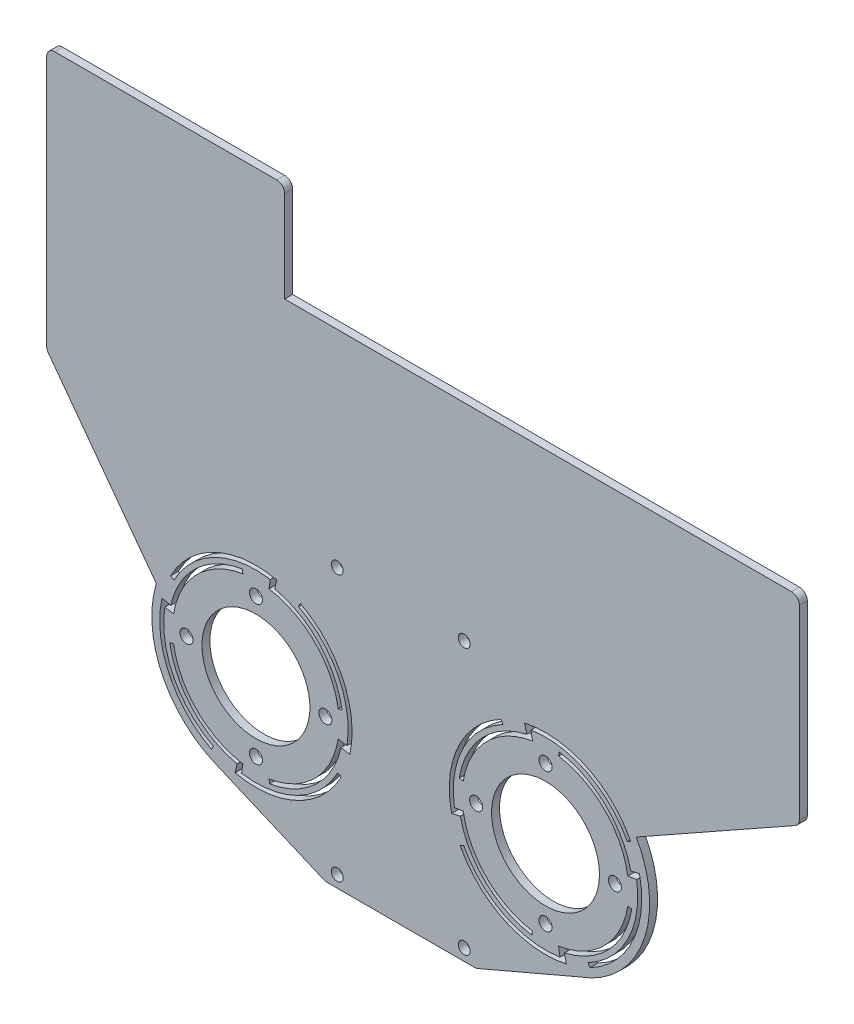
SolidWorks part; units mm, degrees
material "Thornel Mat VMA"
ref_plane "前视基准面" through (0, 0, 0) normal (0, 0, 1) x (1, 0, 0)
ref_plane "上视基准面" through (0, 0, 0) normal (0, 1, 0) x (1, 0, 0)
ref_plane "右视基准面" through (0, 0, 0) normal (1, 0, 0) x (0, 0, -1)
other "Configuration Table"
sketch "草图1" plane through (0, 0, 0) normal (0, 0, 1) x (1, 0, 0)
  line L0 (0, 0) -> (0, -46.0913) construction
  circle A0 centre (36.5, 0) radius 13.6
  circle A2 centre (36.5, 0) radius 21
  circle A5 centre (36.5, 0) radius 17.5 construction
  circle A6 centre (19, 0) radius 1.65
  circle A7 centre (36.5, 17.5) radius 1.65
  circle A8 centre (54, 0) radius 1.65
  circle A9 centre (36.5, -17.5) radius 1.65
  circle A14 centre (-36.5, 0) radius 17.5 construction
  circle A15 centre (-36.5, -17.5) radius 1.65
  circle A16 centre (-54, 0) radius 1.65
  circle A17 centre (-36.5, 17.5) radius 1.65
  circle A18 centre (-19, 0) radius 1.65
  circle A19 centre (-36.5, 0) radius 21
  circle A20 centre (-36.5, 0) radius 13.6
  point P20 (36.5, 0)
  point P28 (-36.5, 0)
  dimension "D3" = 42
  dimension "D4" = 27.2
  dimension "D5" = 35
  dimension "D6" = 4
  dimension "D1" = 73
  dimension "D2" = 36.5
extrude "凸台-拉伸1" add sketch "草图1" along normal blind 2
sketch "草图2" plane through (0, 0, 0) normal (0, 0, 1) x (1, 0, 0)
  line L0 (0, 0) -> (91.6352, 0) construction
  line L1 (36.5, 42.5304) -> (36.5, -42.8939) construction
  line L2 (39.9416, 21.7291) -> (39.7851, 20.7415)
  line L3 (32.8629, 22.9638) -> (33.2149, 20.7415)
  line L4 (36.5, 0) -> (21.2631, 41.8632) construction
  line L5 (31.2513, 23.6752) -> (31.7383, 21.4785)
  line L6 (25.3026, 21.51) -> (25.7643, 20.623)
  line L7 (58.2291, -3.4416) -> (57.2415, -3.2851)
  line L8 (59.4638, 3.6371) -> (57.2415, 3.2851)
  line L9 (33.0584, -21.7291) -> (33.2149, -20.7415)
  line L10 (40.1371, -22.9638) -> (39.7851, -20.7415)
  line L11 (14.7709, -3.4416) -> (15.7585, -3.2851)
  line L12 (13.5362, -3.6371) -> (14.7709, -3.4416)
  line L13 (58.01, 11.1974) -> (57.123, 10.7357)
  line L14 (60.1752, 5.2487) -> (57.9785, 4.7617)
  line L15 (47.6974, -21.51) -> (47.2357, -20.623)
  line L16 (41.7487, -23.6752) -> (41.2617, -21.4785)
  line L17 (14.99, -11.1974) -> (15.877, -10.7357)
  line L18 (12.8248, -5.2487) -> (15.0215, -4.7617)
  line L19 (14.7709, 3.4416) -> (15.7585, 3.2851) [skipped]
  line L20 (14.7709, 3.4416) -> (15.7585, 3.2851)
  line L21 (0, 0) -> (0, -44.0101) construction
  line L22 (-14.7709, 3.4416) -> (-15.7585, 3.2851)
  line L23 (-12.8248, -5.2487) -> (-15.0215, -4.7617)
  line L24 (-14.99, -11.1974) -> (-15.877, -10.7357)
  line L25 (-41.7487, -23.6752) -> (-41.2617, -21.4785)
  line L26 (-47.6974, -21.51) -> (-47.2357, -20.623)
  line L27 (-60.1752, 5.2487) -> (-57.9785, 4.7617)
  line L28 (-58.01, 11.1974) -> (-57.123, 10.7357)
  line L29 (-13.5362, -3.6371) -> (-14.7709, -3.4416)
  line L30 (-14.7709, -3.4416) -> (-15.7585, -3.2851)
  line L31 (-40.1371, -22.9638) -> (-39.7851, -20.7415)
  line L32 (-33.0584, -21.7291) -> (-33.2149, -20.7415)
  line L33 (-59.4638, 3.6371) -> (-57.2415, 3.2851)
  line L34 (-58.2291, -3.4416) -> (-57.2415, -3.2851)
  line L35 (-25.3026, 21.51) -> (-25.7643, 20.623)
  line L36 (-31.2513, 23.6752) -> (-31.7383, 21.4785)
  line L37 (-32.8629, 22.9638) -> (-33.2149, 20.7415)
  line L38 (-39.9416, 21.7291) -> (-39.7851, 20.7415)
  circle A0 centre (36.5, 0) radius 21
  arc A1 (14.99, -11.1974) -> (41.7487, -23.6752) centre (36.5, 0) ccw
  arc A2 (25.7643, 20.623) -> (13.5362, -3.6371) centre (36.5, 0) ccw
  arc A3 (15.0215, -4.7617) -> (33.0584, -21.7291) centre (36.5, 0) ccw
  circle A4 centre (36.5, 0) radius 26.25
  arc A5 (41.2617, -21.4785) -> (58.2291, -3.4416) centre (36.5, 0) ccw
  arc A6 (57.9785, 4.7617) -> (39.9416, 21.7291) centre (36.5, 0) ccw
  arc A7 (15.877, -10.7357) -> (40.1371, -22.9638) centre (36.5, 0) ccw
  arc A8 (47.2357, -20.623) -> (59.4638, 3.6371) centre (36.5, 0) ccw
  arc A9 (57.123, 10.7357) -> (32.8629, 22.9638) centre (36.5, 0) ccw
  arc A10 (31.7383, 21.4785) -> (14.7709, 3.4416) centre (36.5, 0) ccw
  arc A11 (15.0215, -4.7617) -> (33.0584, -21.7291) centre (36.5, 0) ccw
  arc A12 (41.2617, -21.4785) -> (58.2291, -3.4416) centre (36.5, 0) ccw
  arc A13 (47.6974, -21.51) -> (31.2513, 23.6752) centre (36.5, 0) ccw
  arc A14 (58.2291, 3.4416) -> (39.9416, 21.7291) centre (36.5, 0) ccw
  arc A15 (25.3026, 21.51) -> (12.8248, -5.2487) centre (36.5, 0) ccw
  arc A16 (-25.3026, 21.51) -> (-12.8248, -5.2487) centre (-36.5, 0) cw
  arc A18 (-58.2291, 3.4416) -> (-39.9416, 21.7291) centre (-36.5, 0) cw
  arc A21 (-47.6974, -21.51) -> (-31.2513, 23.6752) centre (-36.5, 0) cw
  arc A22 (-41.2617, -21.4785) -> (-58.2291, -3.4416) centre (-36.5, 0) cw
  arc A23 (-15.0215, -4.7617) -> (-33.0584, -21.7291) centre (-36.5, 0) cw
  arc A24 (-31.7383, 21.4785) -> (-14.7709, 3.4416) centre (-36.5, 0) cw
  arc A29 (-57.123, 10.7357) -> (-32.8629, 22.9638) centre (-36.5, 0) cw
  arc A30 (-47.2357, -20.623) -> (-59.4638, 3.6371) centre (-36.5, 0) cw
  arc A33 (-15.877, -10.7357) -> (-40.1371, -22.9638) centre (-36.5, 0) cw
  arc A34 (-57.9785, 4.7617) -> (-39.9416, 21.7291) centre (-36.5, 0) cw
  arc A35 (-41.2617, -21.4785) -> (-58.2291, -3.4416) centre (-36.5, 0) cw
  circle A36 centre (-36.5, 0) radius 26.25
  arc A37 (-15.0215, -4.7617) -> (-33.0584, -21.7291) centre (-36.5, 0) cw
  arc A38 (-25.7643, 20.623) -> (-13.5362, -3.6371) centre (-36.5, 0) cw
  arc A39 (-14.99, -11.1974) -> (-41.7487, -23.6752) centre (-36.5, 0) cw
  circle A40 centre (-36.5, 0) radius 21
  point P34 (36.5, 0)
  point P50 (36.5, 0)
  point P86 (-36.5, 0)
  point P87 (-36.5, 0)
  dimension "D1" = 52.5
  dimension "D2" = 48.5
  dimension "D3" = 46.5
  dimension "D4" = 44
  dimension "D5" = 9
  dimension "D6" = 9
  dimension "D7" = 20
  dimension "D8" = 7.5
  dimension "D9" = 7.5
  dimension "D10" = 4
  dimension "D12" = 9
  dimension "D11" = 4
extrude "凸台-拉伸3" add sketch "草图2" along normal blind 2 contours A4 A15 L6 A2 L12 L11 A0 L20 A10 L5 A13 L15 A8 L8 L7 A5 L16 A1 L17 A7 L10 L9 A3 L18 | L14 A13 L13 A9 L3 A0 L2 A6 | A36 L32 A40 L31 A33 L24 A39 L25 A22 L34 L33 A30 L26 A21 L36 A24 L22 L30 L29 A38 L35 A16 L23 A23 | L38 A40 L37 A29 L28 A21 L27 A18
sketch "草图3" plane through (0, 0, 0) normal (0, 0, 1) x (1, 0, 0)
  line L0 (0, 0) -> (0, 86)
  line L1 (-29.25, 86) -> (29.25, 86)
  line L2 (29.25, 86) -> (100.5, 86)
  line L3 (100.5, 86) -> (100.5, 36)
  line L4 (-29.25, 86) -> (-29.25, 111)
  line L5 (-29.25, 111) -> (-89.25, 111)
  line L6 (-89.25, 111) -> (-89.25, 45)
  line L7 (-89.25, 45) -> (-61.597, 7.6943)
  line L8 (100.5, 36) -> (59.3789, 12.8694)
  line L9 (0, 0) -> (0, -36)
  line L10 (0, -36) -> (19, -36)
  line L11 (19, -36) -> (48.3955, -23.4)
  line L12 (0, -36) -> (-19, -36)
  line L13 (-19, -36) -> (-46.797, -24.1461)
  circle A0 centre (-36.5, 0) radius 26.25
  circle A1 centre (36.5, 0) radius 26.25
  point P5 (0, 86)
  dimension "D1" = 58.5
  dimension "D2" = 71.25
  dimension "D3" = 25
  dimension "D4" = 60
  dimension "D5" = 66
  dimension "D6" = 86
  dimension "D7" = 50
  dimension "D8" = 36
extrude "凸台-拉伸4" add sketch "草图3" along normal blind 2 contours A0 L13 L12 L9 L0 L1 L4 L5 L6 L7 | A1 L8 L3 L2 L1 L0 L9 L10 L11
fillet "圆角1" radius 2 7 edges at (100.5, 86, 1) (100.5, 36, 1) (19, -36, 1) (-19, -36, 1) (-89.25, 45, 1) (-89.25, 111, 1) (-29.25, 111, 1)
sketch "草图4" plane through (0, 0, 2) normal (0, 0, 1) x (1, 0, 0)
  line L0 (18.5894, -36) -> (-18.5914, -36) construction
  circle A0 centre (-16, -33) radius 1.5
  circle A1 centre (16, -33) radius 1.5
  circle A2 centre (-16, 34) radius 1.5
  circle A3 centre (16, 34) radius 1.5
  dimension "D3" = 3
  dimension "D4" = 3
  dimension "D5" = 3
  dimension "D1" = 32
  dimension "D2" = 16
  dimension "D6" = 2
extrude "切除-拉伸1" cut sketch "草图4" against normal blind 2
